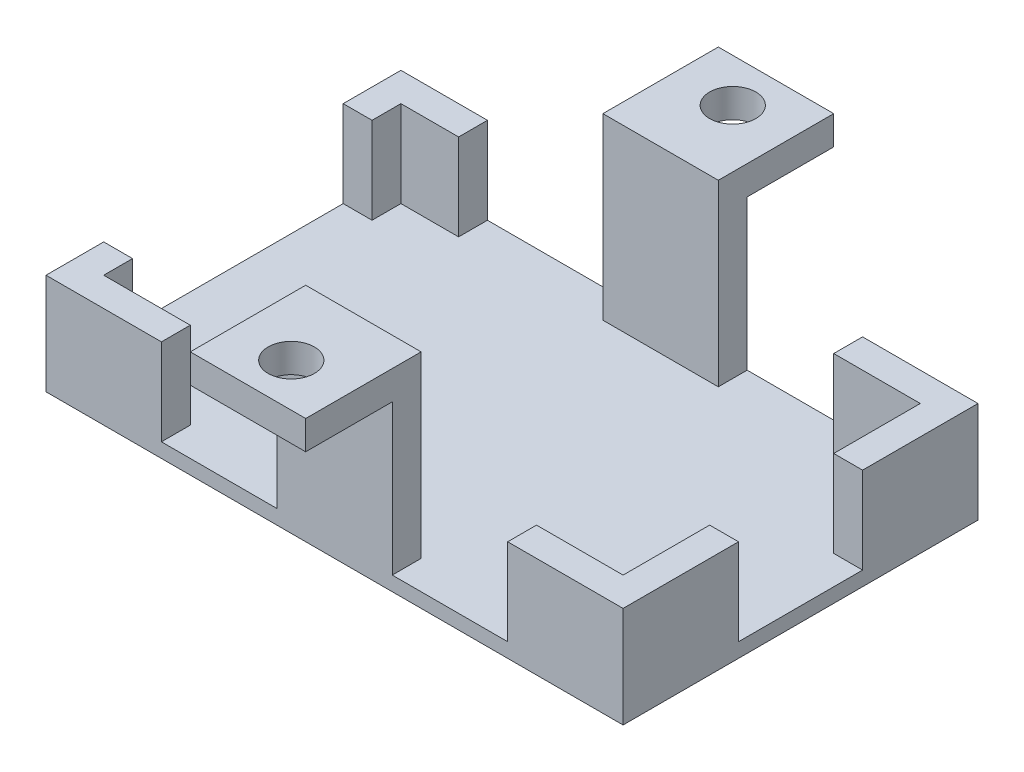
SolidWorks part; units mm, degrees
ref_plane "Front Plane" through (0, 0, 0) normal (0, 0, 1) x (1, 0, 0)
ref_plane "Top Plane" through (0, 0, 0) normal (0, 1, 0) x (1, 0, 0)
ref_plane "Right Plane" through (0, 0, 0) normal (1, 0, 0) x (0, 0, -1)
sketch "Sketch1" plane through (0, 0, 0) normal (0, 1, 0) x (1, 0, 0)
  line L1 (-25.4, -15.621) -> (25.4, -15.621)
  line L2 (-25.4, -15.621) -> (-25.4, 15.621)
  line L3 (-25.4, 15.621) -> (25.4, 15.621)
  line L4 (25.4, -15.621) -> (25.4, 15.621)
  line L5 (-25.4, -15.621) -> (25.4, 15.621) construction
  line L6 (-25.4, 15.621) -> (25.4, -15.621) construction
  point P0 (0, 0)
  dimension "D1" = 50.8
  dimension "D2" = 31.242
extrude "Boss-Extrude1" add sketch "Sketch1" along normal blind 1.27
sketch "Sketch2" plane through (0, 1.27, 0) normal (0, 1, 0) x (1, 0, 0)
  line L0 (-25.4, 10.541) -> (-22.86, 10.541)
  line L1 (-25.4, 15.621) -> (-25.4, -15.621) construction
  line L2 (-22.86, 10.541) -> (-22.86, 13.081)
  line L3 (-22.86, 13.081) -> (-17.78, 13.081)
  line L4 (-17.78, 13.081) -> (-17.78, 15.621)
  line L5 (25.4, 15.621) -> (-25.4, 15.621) construction
  line L6 (-17.78, 15.621) -> (-25.4, 15.621)
  line L7 (-25.4, 15.621) -> (-25.4, 10.541)
  line L8 (-25.4, -10.541) -> (-22.86, -10.541)
  line L9 (-22.86, -10.541) -> (-22.86, -13.081)
  line L10 (-22.86, -13.081) -> (-15.24, -13.081)
  line L11 (-15.24, -13.081) -> (-15.24, -15.621)
  line L12 (-25.4, -15.621) -> (25.4, -15.621) construction
  line L13 (-15.24, -15.621) -> (-25.4, -15.621)
  line L14 (-25.4, -15.621) -> (-25.4, -10.541)
  line L15 (15.24, 15.621) -> (25.4, 15.621)
  line L16 (25.4, 15.621) -> (25.4, 5.461)
  line L17 (25.4, -15.621) -> (25.4, 15.621) construction
  line L18 (25.4, 5.461) -> (22.86, 5.461)
  line L19 (22.86, 5.461) -> (22.86, 13.081)
  line L20 (22.86, 13.081) -> (15.24, 13.081)
  line L21 (15.24, 13.081) -> (15.24, 15.621)
  line L22 (25.4, -5.461) -> (25.4, -15.621)
  line L23 (25.4, -15.621) -> (15.24, -15.621)
  line L24 (15.24, -15.621) -> (15.24, -13.081)
  line L25 (15.24, -13.081) -> (22.86, -13.081)
  line L26 (22.86, -13.081) -> (22.86, -5.461)
  line L27 (22.86, -5.461) -> (25.4, -5.461)
  point P36 (15.24, 14.351)
  dimension "D1" = 2.54
  dimension "D2" = 2.54
  dimension "D3" = 2.54
  dimension "D4" = 2.54
  dimension "D5" = 7.62
  dimension "D6" = 5.08
  dimension "D7" = 5.08
  dimension "D8" = 7.62
  dimension "D9" = 2.54
  dimension "D10" = 2.54
  dimension "D11" = 2.54
  dimension "D12" = 2.54
  dimension "D13" = 7.62
  dimension "D14" = 7.62
  dimension "D15" = 7.62
  dimension "D16" = 7.62
extrude "Boss-Extrude2" add sketch "Sketch2" along normal blind 7.62
sketch "Sketch3" plane through (0, 0, 0) normal (1, 0, 0) x (0, 0, -1)
  line L8 (-13.081, 0) -> (-15.621, 0)
  line L10 (-15.621, 0) -> (-15.621, 14.478)
  line L11 (-15.621, 14.478) -> (-23.241, 14.478)
  line L12 (-23.241, 14.478) -> (-23.241, 17.018)
  line L13 (-23.241, 17.018) -> (-13.081, 17.018)
  line L14 (-13.081, 17.018) -> (-13.081, 0)
  line L17 (-15.621, 8.89) -> (-15.621, 1.27) construction
  dimension "D1" = 2.54
  dimension "D2" = 17.018
  dimension "0.05" = 2.54
  dimension "D3" = 10.16
extrude "Boss-Extrude3" add sketch "Sketch3" along normal mid plane 10.16
sketch "Sketch4" plane through (0, 14.478, 0) normal (0, -1, 0) x (1, 0, 0)
  line L0 (0, -9.3599) -> (0, 9.3599) construction
  line L1 (5.08, 23.241) -> (-5.08, 23.241) construction
  circle A0 centre (0, 19.431) radius 2.032
  dimension "D1" = 4.064
  dimension "D2" = 3.81
extrude "Cut-Extrude1" cut sketch "Sketch4" against normal blind 7.62
mirror "Mirror2" about plane through (0, 0, 0) normal (0, 0, 1) of "Boss-Extrude3"
mirror "Mirror1" about plane through (0, 0, 0) normal (0, 0, 1) of "Cut-Extrude1"
